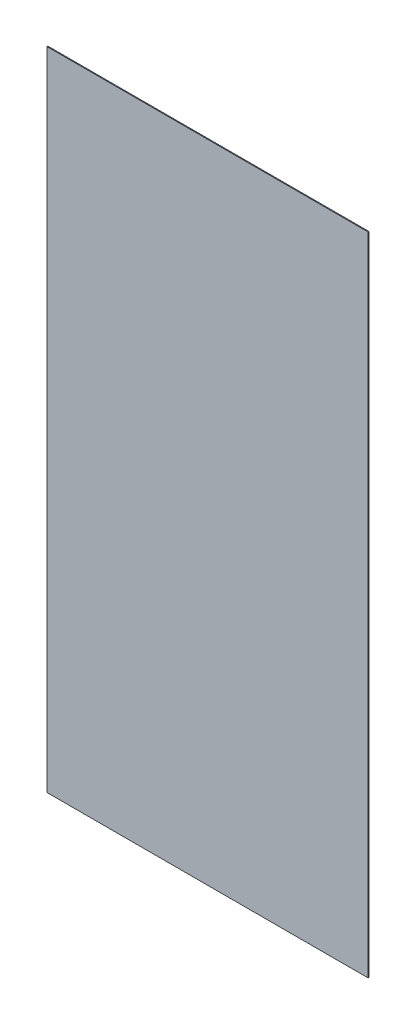
SolidWorks part; units mm, degrees
material "Acrylic (Medium-high impact)"
ref_plane "Front Plane" through (0, 0, 0) normal (0, 0, 1) x (1, 0, 0)
ref_plane "Top Plane" through (0, 0, 0) normal (0, 1, 0) x (1, 0, 0)
ref_plane "Right Plane" through (0, 0, 0) normal (1, 0, 0) x (0, 0, -1)
sketch "Sketch1" plane through (0, 0, 0) normal (0, 0, 1) x (1, 0, 0)
  line L1 (0, 0) -> (603.25, 0)
  line L2 (0, 0) -> (0, 1212.85)
  line L3 (0, 1212.85) -> (603.25, 1212.85)
  line L4 (603.25, 0) -> (603.25, 1212.85)
  dimension "D1" = 603.25
  dimension "D2" = 1212.85
extrude "Boss-Extrude1" add sketch "Sketch1" along normal blind 1.651
